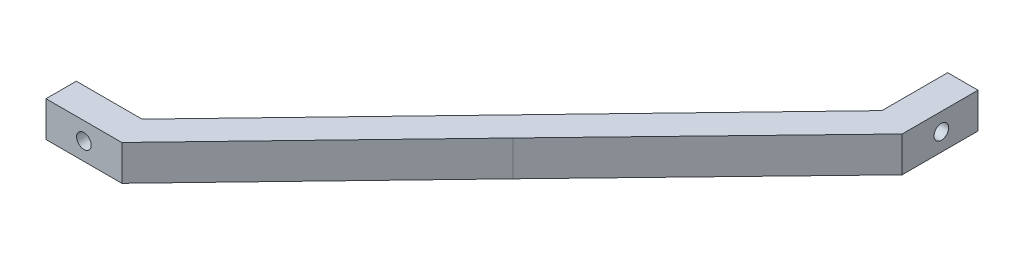
SolidWorks part; units mm, degrees
ref_plane "Front Plane" through (0, 0, 0) normal (0, 0, 1) x (1, 0, 0)
ref_plane "Top Plane" through (0, 0, 0) normal (0, 1, 0) x (1, 0, 0)
ref_plane "Right Plane" through (0, 0, 0) normal (1, 0, 0) x (0, 0, -1)
sketch "Sketch12" plane through (0, 0, 0) normal (0, 1, 0) x (1, 0, 0)
  line L0 (85.5226, 6.5) -> (85.5226, -8.5)
  line L3 (-5.2074, -87.15) -> (9.7926, -87.15)
  line L6 (43.6576, -43.825) -> (7.7926, -81.15)
  line L8 (79.5226, -6.5) -> (79.5226, 6.5)
  line L9 (79.5226, 6.5) -> (85.5226, 6.5)
  line L10 (-5.2074, -87.15) -> (-5.2074, -81.15)
  line L11 (-5.2074, -81.15) -> (7.7926, -81.15)
  line L15 (0, 0) -> (43.6576, -43.825) construction
  line L16 (9.7926, -87.15) -> (47.6951, -47.7046)
  line L17 (85.5226, -8.5) -> (47.6951, -47.7046)
  line L18 (79.5226, -6.5) -> (43.6576, -43.825)
  dimension "D1" = 6
  dimension "D2" = 61.8596
  dimension "D5" = 54.7041
  dimension "D6" = 13
  dimension "D7" = 13
  dimension "D3" = 15
  dimension "D4" = 15
  dimension "D8" = 51.7634
  dimension "D9" = 51.7634
  dimension "D10" = 54.4786
extrude "Boss-Extrude1" add sketch "Sketch12" along normal blind 7
sketch "Sketch14" plane through (0, 0, 81.15) normal (0, 0, -1) x (-1, 0, 0)
  line L0 (-7.7926, 7) -> (5.2074, 7) construction
  line L2 (5.2074, 7) -> (5.2074, 0) construction
  circle A0 centre (-2.2926, 3.5) radius 1.45
  dimension "D1" = 3.5
  dimension "D2" = 2.9
  dimension "D3" = 7.5
extrude "Cut-Extrude1" cut sketch "Sketch14" against normal blind 10
sketch "Sketch15" plane through (79.5226, 0, 0) normal (-1, 0, 0) x (0, 0, 1)
  line L0 (-6.5, 7) -> (6.5, 7) construction
  line L1 (-6.5, 7) -> (-6.5, 0) construction
  circle A0 centre (0.75, 3.5) radius 1.45
  dimension "D2" = 2.9
  dimension "D1" = 3.5
  dimension "D3" = 7.25
extrude "Cut-Extrude2" cut sketch "Sketch15" against normal blind 10
